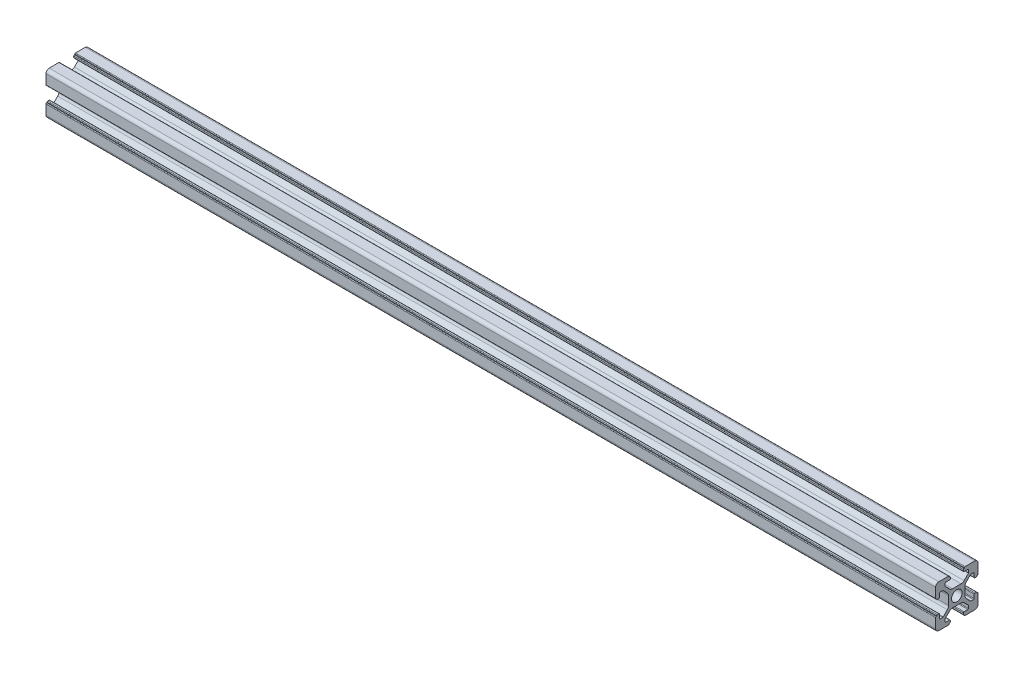
SolidWorks part; units mm, degrees
material "6061 Alloy"
ref_plane "Front Plane" through (0, 0, 0) normal (0, 0, 1) x (1, 0, 0)
ref_plane "Top Plane" through (0, 0, 0) normal (0, 1, 0) x (1, 0, 0)
ref_plane "Right Plane" through (0, 0, 0) normal (1, 0, 0) x (0, 0, -1)
sketch "Sketch1" plane through (0, 0, 0) normal (0, 0, 1) x (1, 0, 0)
  line L0 (-210, 0) -> (210, 0)
  dimension "D1" = 420
other "铝型材 2020(1)"
ref_plane "Plane1" through (-210, 0, 0) normal (1, 0, 0) x (0, 1, 0)
sketch "草图11" plane through (-210, 0, 0) normal (1, 0, 0) x (0, 1, 0)
  line L0 (3.9, 0) -> (3.9, -2.0109)
  line L1 (4.4858, -3.4251) -> (6.5607, -5.5)
  line L2 (6.5607, -5.5) -> (7.9, -5.5)
  line L3 (8.2, -5.2) -> (8.2, -3.4)
  line L4 (8.5, -3.1) -> (9.2, -3.1)
  line L5 (9.5, -3.4) -> (9.5, -3.6)
  line L6 (9.5, -3.6) -> (9.7, -3.6)
  line L7 (10, -3.9) -> (10, -8.5)
  line L8 (8.5, -10) -> (3.9, -10)
  line L9 (3.1, -9.2) -> (3.1, -8.5)
  line L10 (3.4, -8.2) -> (5.2, -8.2)
  line L11 (5.5, -7.9) -> (5.5, -6.6849)
  line L12 (5.4121, -6.4728) -> (3.4251, -4.4858)
  line L13 (2.0109, -3.9) -> (0, -3.9)
  line L14 (0, -3.9) -> (-2.0109, -3.9)
  line L15 (-3.4251, -4.4858) -> (-5.4121, -6.4728)
  line L16 (-5.5, -6.6849) -> (-5.5, -7.9)
  line L17 (-5.2, -8.2) -> (-3.4, -8.2)
  line L18 (-3.1, -8.5) -> (-3.1, -9.2)
  line L19 (-3.9, -10) -> (-8.5, -10)
  line L20 (-10, -8.5) -> (-10, -3.9)
  line L21 (-9.7, -3.6) -> (-9.5, -3.6)
  line L22 (-9.5, -3.6) -> (-9.5, -3.4)
  line L23 (-9.2, -3.1) -> (-8.5, -3.1)
  line L24 (-8.2, -3.4) -> (-8.2, -5.2)
  line L25 (-7.9, -5.5) -> (-6.6849, -5.5)
  line L26 (-6.4728, -5.4121) -> (-4.4858, -3.4251)
  line L27 (-3.9, -2.0109) -> (-3.9, 0)
  line L28 (-3.9, 0) -> (-3.9, 2.0109)
  line L29 (-4.4858, 3.4251) -> (-6.4728, 5.4121)
  line L30 (-6.6849, 5.5) -> (-7.9, 5.5)
  line L31 (-8.2, 5.2) -> (-8.2, 3.4)
  line L32 (-8.5, 3.1) -> (-9.2, 3.1)
  line L33 (-9.5, 3.4) -> (-9.5, 3.6)
  line L34 (-9.5, 3.6) -> (-9.7, 3.6)
  line L35 (-10, 3.9) -> (-10, 8.5)
  line L36 (-8.5, 10) -> (-3.9, 10)
  line L37 (-3.6, 9.7) -> (-3.6, 9.5)
  line L38 (-3.6, 9.5) -> (-3.4, 9.5)
  line L39 (-3.1, 9.2) -> (-3.1, 8.5)
  line L40 (-3.4, 8.2) -> (-5.2, 8.2)
  line L41 (-5.5, 7.9) -> (-5.5, 6.6849)
  line L42 (-5.4121, 6.4728) -> (-3.4251, 4.4858)
  line L43 (-2.0109, 3.9) -> (0, 3.9)
  line L44 (0, 3.9) -> (2.0109, 3.9)
  line L45 (3.4251, 4.4858) -> (5.4121, 6.4728)
  line L46 (5.5, 6.6849) -> (5.5, 7.9)
  line L47 (5.2, 8.2) -> (3.4, 8.2)
  line L48 (3.1, 8.5) -> (3.1, 9.2)
  line L49 (3.4, 9.5) -> (3.6, 9.5)
  line L50 (3.6, 9.5) -> (3.6, 9.7)
  line L51 (3.9, 10) -> (8.5, 10)
  line L52 (10, 8.5) -> (10, 3.9)
  line L53 (9.7, 3.6) -> (9.5, 3.6)
  line L54 (9.5, 3.6) -> (9.5, 3.4)
  line L55 (9.2, 3.1) -> (8.5, 3.1)
  line L56 (8.2, 3.4) -> (8.2, 5.2)
  line L57 (7.9, 5.5) -> (6.6849, 5.5)
  line L58 (6.4728, 5.4121) -> (4.4858, 3.4251)
  line L59 (3.9, 2.0109) -> (3.9, 0)
  circle A0 centre (0, 0) radius 2.5
  arc A1 (3.9, -2.0109) -> (4.4858, -3.4251) centre (5.9, -2.0109) ccw
  arc A2 (7.9, -5.5) -> (8.2, -5.2) centre (7.9, -5.2) ccw
  arc A3 (8.5, -3.1) -> (8.2, -3.4) centre (8.5, -3.4) ccw
  arc A4 (9.5, -3.4) -> (9.2, -3.1) centre (9.2, -3.4) ccw
  arc A5 (10, -3.9) -> (9.7, -3.6) centre (9.7, -3.9) ccw
  arc A6 (8.5, -10) -> (10, -8.5) centre (8.5, -8.5) ccw
  arc A7 (3.6, -9.7) -> (3.9, -10) centre (3.9, -9.7) ccw
  arc A8 (3.6, -9.7) -> (3.4, -9.5) centre (3.4, -9.7) ccw
  arc A9 (3.1, -9.2) -> (3.4, -9.5) centre (3.4, -9.2) ccw
  arc A10 (3.4, -8.2) -> (3.1, -8.5) centre (3.4, -8.5) ccw
  arc A11 (5.2, -8.2) -> (5.5, -7.9) centre (5.2, -7.9) ccw
  arc A12 (5.5, -6.6849) -> (5.4121, -6.4728) centre (5.2, -6.6849) ccw
  arc A13 (3.4251, -4.4858) -> (2.0109, -3.9) centre (2.0109, -5.9) ccw
  arc A14 (-2.0109, -3.9) -> (-3.4251, -4.4858) centre (-2.0109, -5.9) ccw
  arc A15 (-5.4121, -6.4728) -> (-5.5, -6.6849) centre (-5.2, -6.6849) ccw
  arc A16 (-5.5, -7.9) -> (-5.2, -8.2) centre (-5.2, -7.9) ccw
  arc A17 (-3.1, -8.5) -> (-3.4, -8.2) centre (-3.4, -8.5) ccw
  arc A18 (-3.4, -9.5) -> (-3.1, -9.2) centre (-3.4, -9.2) ccw
  arc A19 (-3.4, -9.5) -> (-3.6, -9.7) centre (-3.4, -9.7) ccw
  arc A20 (-3.9, -10) -> (-3.6, -9.7) centre (-3.9, -9.7) ccw
  arc A21 (-10, -8.5) -> (-8.5, -10) centre (-8.5, -8.5) ccw
  arc A22 (-9.7, -3.6) -> (-10, -3.9) centre (-9.7, -3.9) ccw
  arc A23 (-9.2, -3.1) -> (-9.5, -3.4) centre (-9.2, -3.4) ccw
  arc A24 (-8.2, -3.4) -> (-8.5, -3.1) centre (-8.5, -3.4) ccw
  arc A25 (-8.2, -5.2) -> (-7.9, -5.5) centre (-7.9, -5.2) ccw
  arc A26 (-6.6849, -5.5) -> (-6.4728, -5.4121) centre (-6.6849, -5.2) ccw
  arc A27 (-4.4858, -3.4251) -> (-3.9, -2.0109) centre (-5.9, -2.0109) ccw
  arc A28 (-3.9, 2.0109) -> (-4.4858, 3.4251) centre (-5.9, 2.0109) ccw
  arc A29 (-6.4728, 5.4121) -> (-6.6849, 5.5) centre (-6.6849, 5.2) ccw
  arc A30 (-7.9, 5.5) -> (-8.2, 5.2) centre (-7.9, 5.2) ccw
  arc A31 (-8.5, 3.1) -> (-8.2, 3.4) centre (-8.5, 3.4) ccw
  arc A32 (-9.5, 3.4) -> (-9.2, 3.1) centre (-9.2, 3.4) ccw
  arc A33 (-10, 3.9) -> (-9.7, 3.6) centre (-9.7, 3.9) ccw
  arc A34 (-8.5, 10) -> (-10, 8.5) centre (-8.5, 8.5) ccw
  arc A35 (-3.6, 9.7) -> (-3.9, 10) centre (-3.9, 9.7) ccw
  arc A36 (-3.1, 9.2) -> (-3.4, 9.5) centre (-3.4, 9.2) ccw
  arc A37 (-3.4, 8.2) -> (-3.1, 8.5) centre (-3.4, 8.5) ccw
  arc A38 (-5.2, 8.2) -> (-5.5, 7.9) centre (-5.2, 7.9) ccw
  arc A39 (-5.5, 6.6849) -> (-5.4121, 6.4728) centre (-5.2, 6.6849) ccw
  arc A40 (-3.4251, 4.4858) -> (-2.0109, 3.9) centre (-2.0109, 5.9) ccw
  arc A41 (2.0109, 3.9) -> (3.4251, 4.4858) centre (2.0109, 5.9) ccw
  arc A42 (5.4121, 6.4728) -> (5.5, 6.6849) centre (5.2, 6.6849) ccw
  arc A43 (5.5, 7.9) -> (5.2, 8.2) centre (5.2, 7.9) ccw
  arc A44 (3.1, 8.5) -> (3.4, 8.2) centre (3.4, 8.5) ccw
  arc A45 (3.4, 9.5) -> (3.1, 9.2) centre (3.4, 9.2) ccw
  arc A46 (3.9, 10) -> (3.6, 9.7) centre (3.9, 9.7) ccw
  arc A47 (10, 8.5) -> (8.5, 10) centre (8.5, 8.5) ccw
  arc A48 (9.7, 3.6) -> (10, 3.9) centre (9.7, 3.9) ccw
  arc A49 (9.2, 3.1) -> (9.5, 3.4) centre (9.2, 3.4) ccw
  arc A50 (8.2, 3.4) -> (8.5, 3.1) centre (8.5, 3.4) ccw
  arc A51 (8.2, 5.2) -> (7.9, 5.5) centre (7.9, 5.2) ccw
  arc A52 (6.6849, 5.5) -> (6.4728, 5.4121) centre (6.6849, 5.2) ccw
  arc A53 (4.4858, 3.4251) -> (3.9, 2.0109) centre (5.9, 2.0109) ccw
  point P0 (-10, 10)
  point P1 (10, 10)
  point P2 (10, -10)
  point P171 (-10, -10)
  point P172 (-10, 0)
  point P173 (10, 0)
  point P174 (0, -10)
  point P175 (0, 10)
  point P176 (0, 0)
  point P177 (0, 0)
